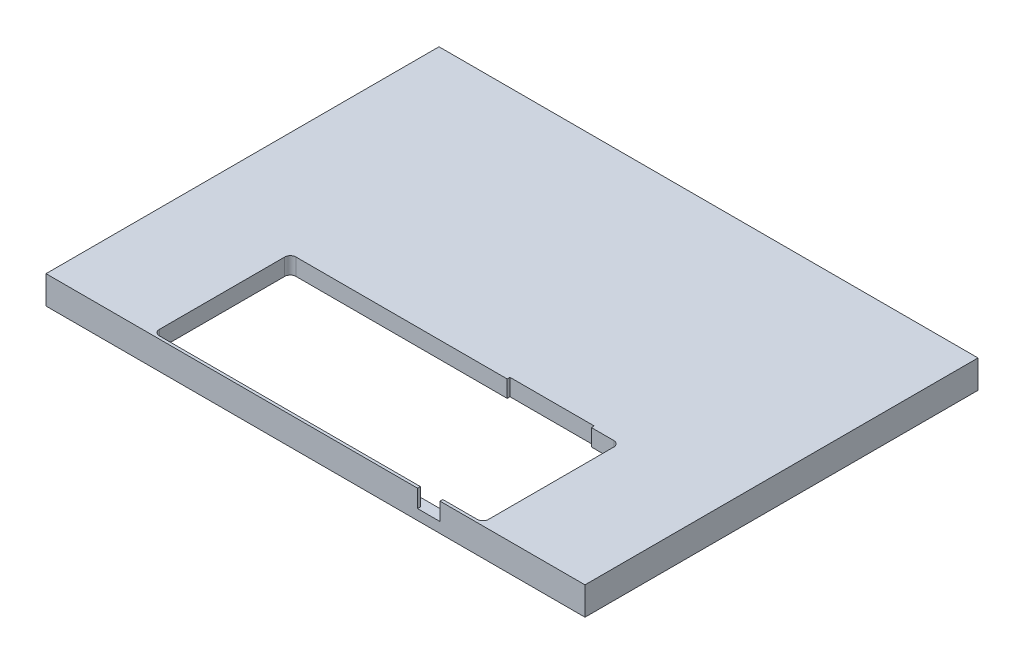
SolidWorks part; units mm, degrees
ref_plane "Front Plane" through (0, 0, 0) normal (0, 0, 1) x (1, 0, 0)
ref_plane "Top Plane" through (0, 0, 0) normal (0, 1, 0) x (1, 0, 0)
ref_plane "Right Plane" through (0, 0, 0) normal (1, 0, 0) x (0, 0, -1)
sketch "Sketch1" plane through (0, 0, 0) normal (0, 1, 0) x (1, 0, 0)
  line L0 (5.08, 5.08) -> (238.76, 5.08)
  line L1 (0, 0) -> (243.84, 0)
  line L2 (0, 0) -> (0, 177.8)
  line L3 (0, 177.8) -> (243.84, 177.8)
  line L4 (243.84, 0) -> (243.84, 177.8)
  line L5 (238.76, 5.08) -> (238.76, 172.72)
  line L6 (5.08, 172.72) -> (238.76, 172.72)
  line L7 (5.08, 5.08) -> (5.08, 172.72)
  dimension "D1" = 177.8
  dimension "D2" = 243.84
  dimension "D3" = 5.08
extrude "Boss-Extrude7" add sketch "Sketch1" along normal blind 12.7
sketch "Sketch6" plane through (0, 12.7, 0) normal (0, 1, 0) x (1, 0, 0)
  line L0 (5.08, 172.72) -> (5.08, 5.08)
  line L1 (5.08, 5.08) -> (238.76, 5.08)
  line L2 (238.76, 5.08) -> (238.76, 172.72)
  line L3 (238.76, 172.72) -> (5.08, 172.72)
extrude "Boss-Extrude8" add sketch "Sketch6" against normal blind 7.62
sketch "Sketch7" plane through (0, 12.7, 0) normal (0, 1, 0) x (1, 0, 0)
  line L0 (0, 0) -> (243.84, 0) construction
  line L1 (0, 177.8) -> (0, 0) construction
  line L2 (243.84, 0) -> (243.84, 177.8) construction
  line L3 (196.37, 1.27) -> (178.2581, 1.27)
  line L4 (47.47, 1.27) -> (47.47, 63.07)
  line L6 (196.37, 63.07) -> (196.37, 1.27)
  line L8 (47.47, 32.17) -> (0, 32.17) construction
  line L9 (196.37, 32.17) -> (243.84, 32.17) construction
  line L11 (168.0981, 0) -> (178.2581, 0)
  line L12 (178.2581, 0) -> (178.2581, 1.27)
  line L14 (157.9954, 1.27) -> (47.47, 1.27)
  line L15 (157.9954, 1.27) -> (168.0981, 1.27)
  line L16 (168.0981, 1.27) -> (168.0981, 0)
  line L18 (183.67, 64.34) -> (145.57, 64.34)
  line L20 (196.37, 63.07) -> (183.67, 63.07)
  line L21 (145.57, 63.07) -> (47.47, 63.07)
  line L22 (183.67, 63.07) -> (183.67, 64.34)
  line L23 (145.57, 63.07) -> (145.57, 64.34)
  dimension "D1" = 1.27
  dimension "D2" = 148.9
  dimension "D3" = 61.8
  dimension "D4" = 10.16
  dimension "D5" = 38.1
  dimension "D6" = 12.7
  dimension "D7" = 1.27
extrude "Cut-Extrude2" cut sketch "Sketch7" against normal blind 8 contours L4 L21 L23 L18 L22 L20 L6 L3 L12 L11 L16 L15 L14
fillet "Fillet1" radius 2.54 4 edges at (47.47, 8.89, -63.07) (47.47, 8.7, -1.27) (196.37, 8.7, -1.27) (196.37, 8.89, -63.07)
